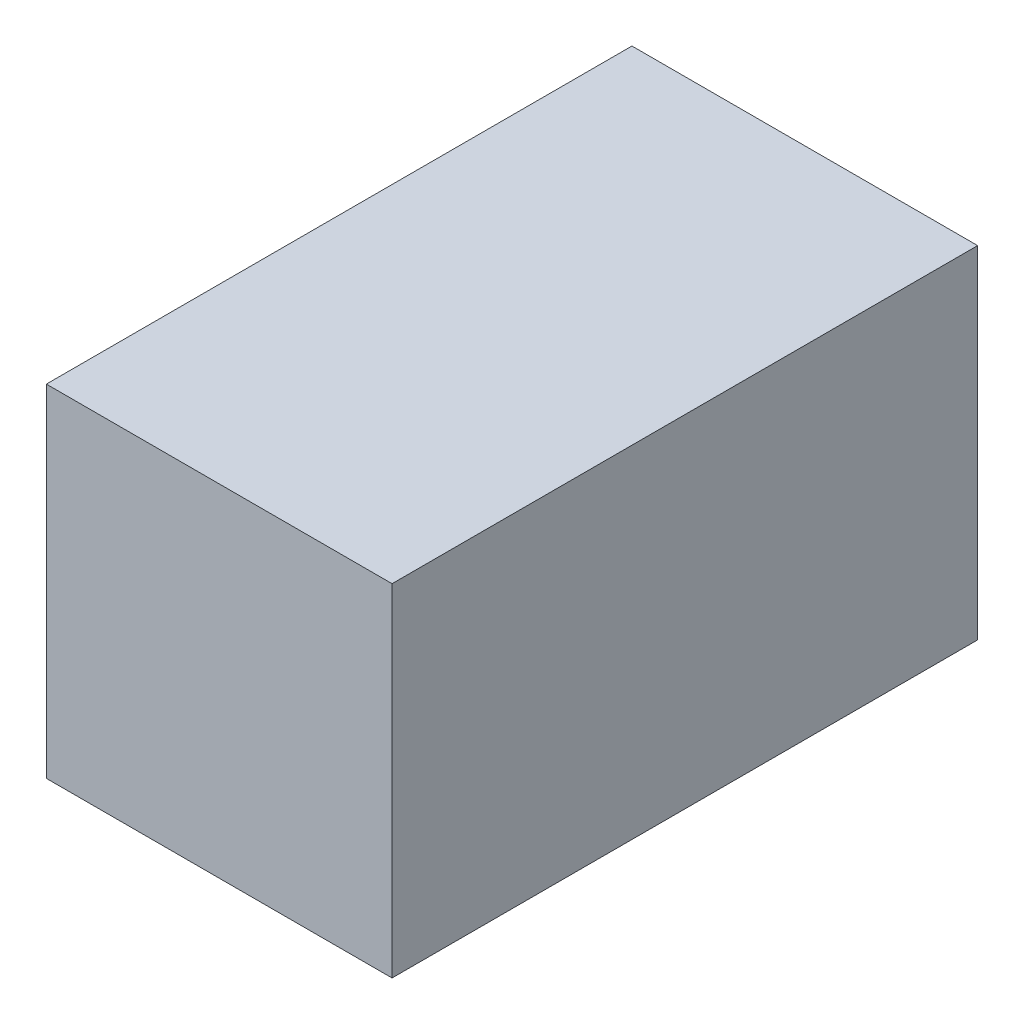
SolidWorks part; units mm, degrees
material "Custom Plastic"
ref_plane "X-Y Datum" through (0, 0, 0) normal (0, 0, 1) x (1, 0, 0)
ref_plane "X-Z Datum" through (0, 0, 0) normal (0, 1, 0) x (1, 0, 0)
ref_plane "Y-Z Datum" through (0, 0, 0) normal (1, 0, 0) x (0, 0, -1)
sketch "Sketch1" plane through (0, 0, 0) normal (0, 0, 1) x (1, 0, 0)
  line L1 (-36.5125, 36.068) -> (36.5125, 36.068)
  line L2 (-36.5125, 36.068) -> (-36.5125, -36.068)
  line L3 (-36.5125, -36.068) -> (36.5125, -36.068)
  line L4 (36.5125, 36.068) -> (36.5125, -36.068)
  line L5 (-36.5125, 36.068) -> (36.5125, -36.068) construction
  line L6 (-36.5125, -36.068) -> (36.5125, 36.068) construction
  circle A0 centre (0, 25.221) radius 8.388 construction
  point P0 (0, 0)
  dimension "D1" = 73.025
  dimension "D2" = 72.136
extrude "Boss-Extrude1" add sketch "Sketch1" along normal blind 123.698
